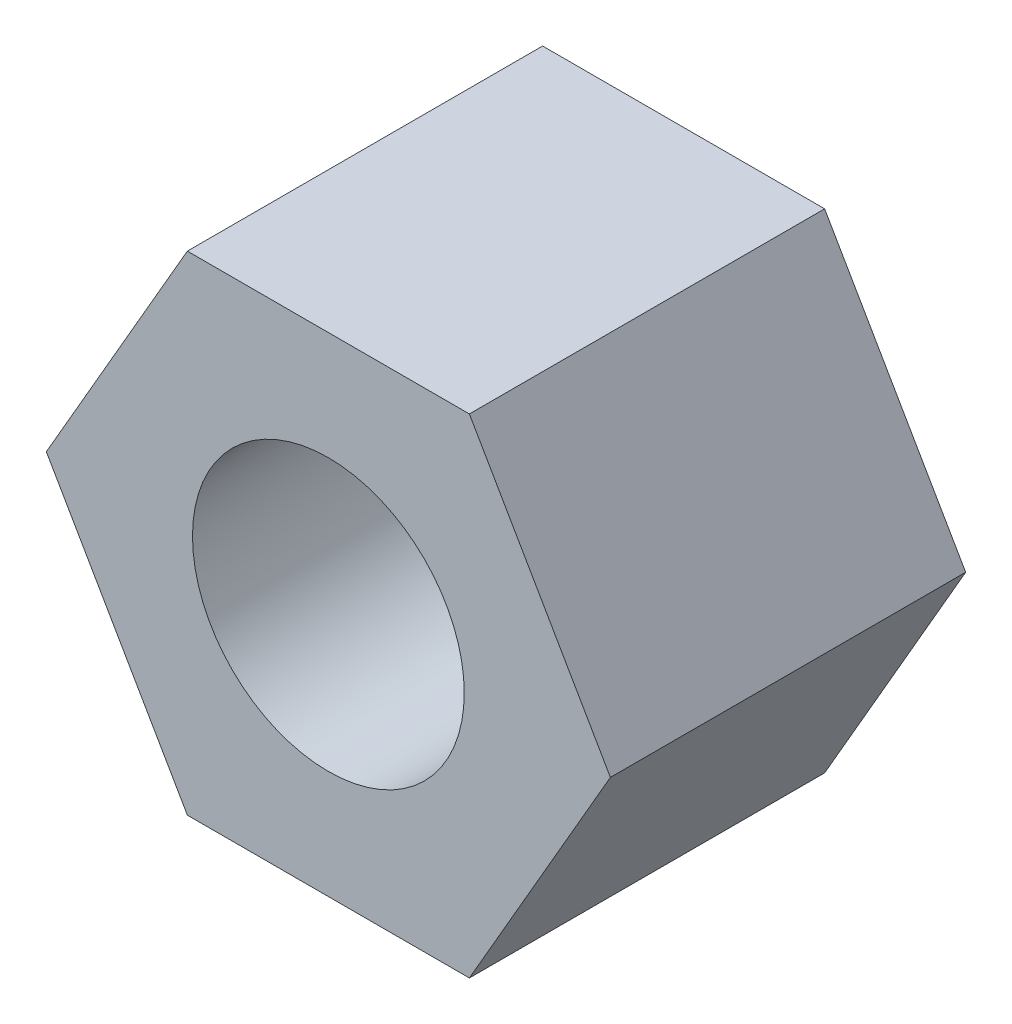
SolidWorks part; units mm, degrees
ref_plane "Front Plane" through (0, 0, 0) normal (0, 0, 1) x (1, 0, 0)
ref_plane "Top Plane" through (0, 0, 0) normal (0, 1, 0) x (1, 0, 0)
ref_plane "Right Plane" through (0, 0, 0) normal (1, 0, 0) x (0, 0, -1)
sketch "S01 - Hexagon and nominal thread envelope" plane through (0, 0, 0) normal (0, 0, 1) x (1, 0, 0)
  line L0 (3.1754, 0) -> (1.5877, 2.75)
  line L1 (1.5877, 2.75) -> (-1.5877, 2.75)
  line L2 (-1.5877, 2.75) -> (-3.1754, 0)
  line L3 (-3.1754, 0) -> (-1.5877, -2.75)
  line L4 (-1.5877, -2.75) -> (1.5877, -2.75)
  line L5 (1.5877, -2.75) -> (3.1754, 0)
  circle A0 centre (0, 0) radius 1.53
  dimension "D1" = 3.06
  dimension "D2" = 1.5877
  dimension "D3" = 3.1754
  dimension "D4" = 1.5877
  dimension "D5" = 3.1754
  dimension "D6" = 2.75
  dimension "D7" = 2.75
extrude "01 - Hexagon and nominal thread envelope" add sketch "S01 - Hexagon and nominal thread envelope" along normal blind 4
